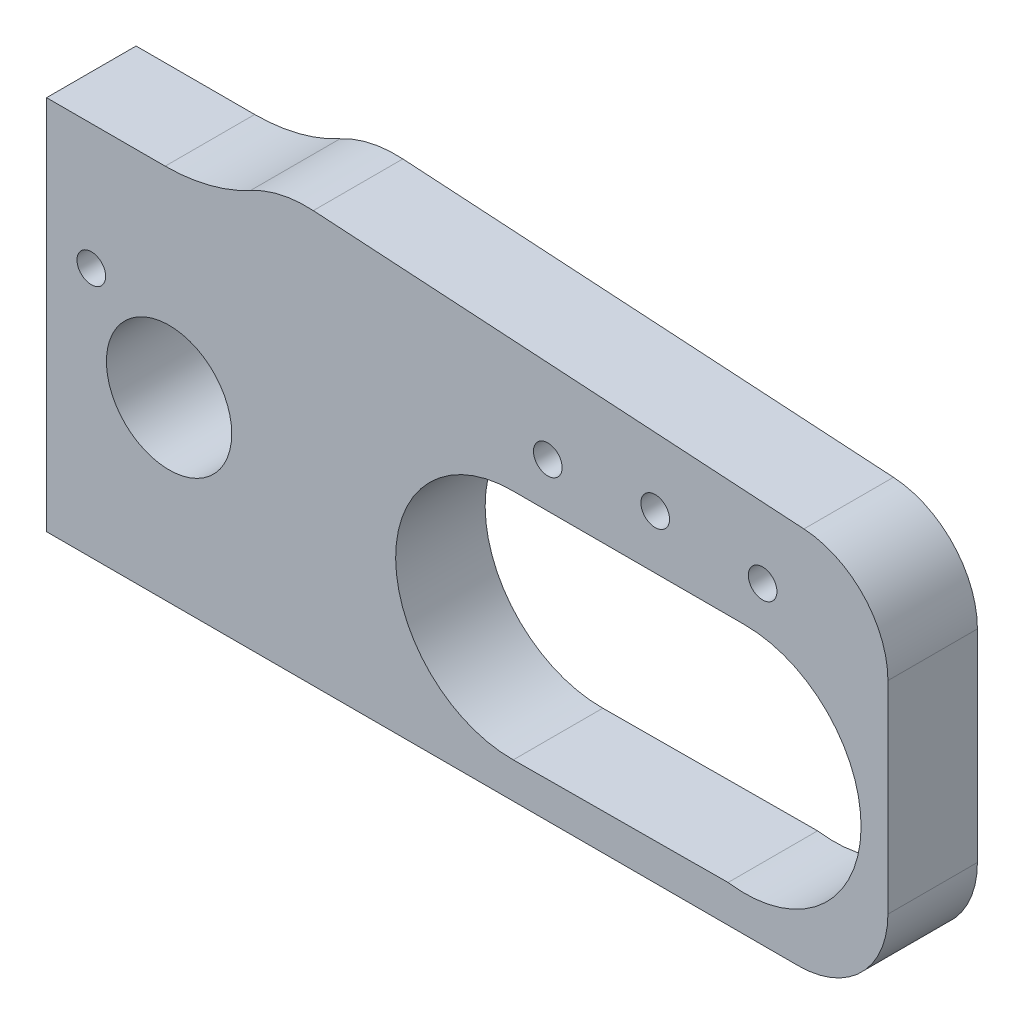
SolidWorks part; units mm, degrees
ref_plane "Front Plane" through (0, 0, 0) normal (1, 0, 0) x (0, 1, 0)
ref_plane "Top Plane" through (0, 0, 0) normal (0, 0, 1) x (0, 1, 0)
ref_plane "Right Plane" through (0, 0, 0) normal (0, 1, 0) x (-1, 0, 0)
sketch "Sketch1" plane through (0, 0, 0) normal (0, 0, 1) x (0, 1, 0)
  line L0 (12.9142, -18.3709) -> (14.6113, 9.0364)
  line L1 (7.9237, -23.0618) -> (-3.3763, -23.0618)
  line L4 (-8.3763, 23.9382) -> (12.6237, 23.9382)
  line L5 (12.6237, 23.9382) -> (12.6237, 17.3122)
  line L7 (-6.3763, -2.0618) -> (-6.2989, -16.0618)
  line L8 (6.6237, -15.0618) -> (6.6237, -2.0618)
  line L10 (-8.3763, 23.9382) -> (-8.3763, -18.0618)
  arc A2 (14.6113, 9.0364) -> (13.8358, 12.54) centre (8.1237, 9.4382) ccw
  arc A3 (12.6237, 17.3122) -> (13.8358, 12.54) centre (22.6237, 17.3122) ccw
  arc A4 (-8.3763, -18.0618) -> (-3.3763, -23.0618) centre (-3.3763, -18.0618) ccw
  arc A5 (7.9237, -23.0618) -> (12.9142, -18.3709) centre (7.9237, -18.0618) ccw
  circle A8 centre (5.6237, 21.4382) radius 0.8
  circle A9 centre (9.1237, -4.0618) radius 0.8
  circle A10 centre (9.6237, -10.0618) radius 0.8
  circle A11 centre (9.1237, -16.0618) radius 0.8
  arc A12 (6.6237, -2.0618) -> (-6.3759, -2.1337) centre (0.1237, -2.0618) ccw
  arc A13 (-6.3096, -14.1329) -> (6.6237, -15.0618) centre (0.1237, -15.0618) ccw
  circle A16 centre (8.1237, 9.4382) radius 5.1
  circle A18 centre (8.1237, 9.4382) radius 5.1
  circle A23 centre (1.537, 17.0949) radius 3.5
  dimension "D8" = 2.5
  dimension "D9" = 1.6
  dimension "D10" = 1.6
  dimension "D11" = 7
  dimension "D1" = 21
  dimension "D2" = 42
  dimension "D3" = 27.4598
  dimension "D4" = 11.3
  dimension "D5" = 2.5
  dimension "D6" = 2.5
  dimension "D7" = 3
extrude "Boss-Extrude1" add sketch "Sketch1" along normal blind 5
sketch "Sketch2" plane through (-23.9382, 0, 0) normal (-1, 0, 0) x (0, -1, 0)
  line L0 (-12.6237, 2.5) -> (-9.6237, 2.5) construction
  line L1 (-12.6237, 5) -> (-12.6237, 0) construction
  line L2 (8.3763, 5) -> (8.3763, 0) construction
  circle A0 centre (-9.6237, 2.5) radius 1.25
  circle A1 centre (2.8763, 2.5) radius 1.25
  dimension "D2" = 5.5
  dimension "D3" = 2.5
  dimension "D4" = 2.5
  dimension "D1" = 3
  dimension "D5" = 0
extrude "Cut-Extrude1" cut sketch "Sketch2" against normal blind 4
sketch "Sketch21" plane through (0, 0, 5) normal (0, 0, 1) x (1, 0, 0)
  circle A0 centre (-9.4382, 8.1237) radius 5.1
extrude "Boss-Extrude2" add sketch "Sketch21" against normal blind 1
